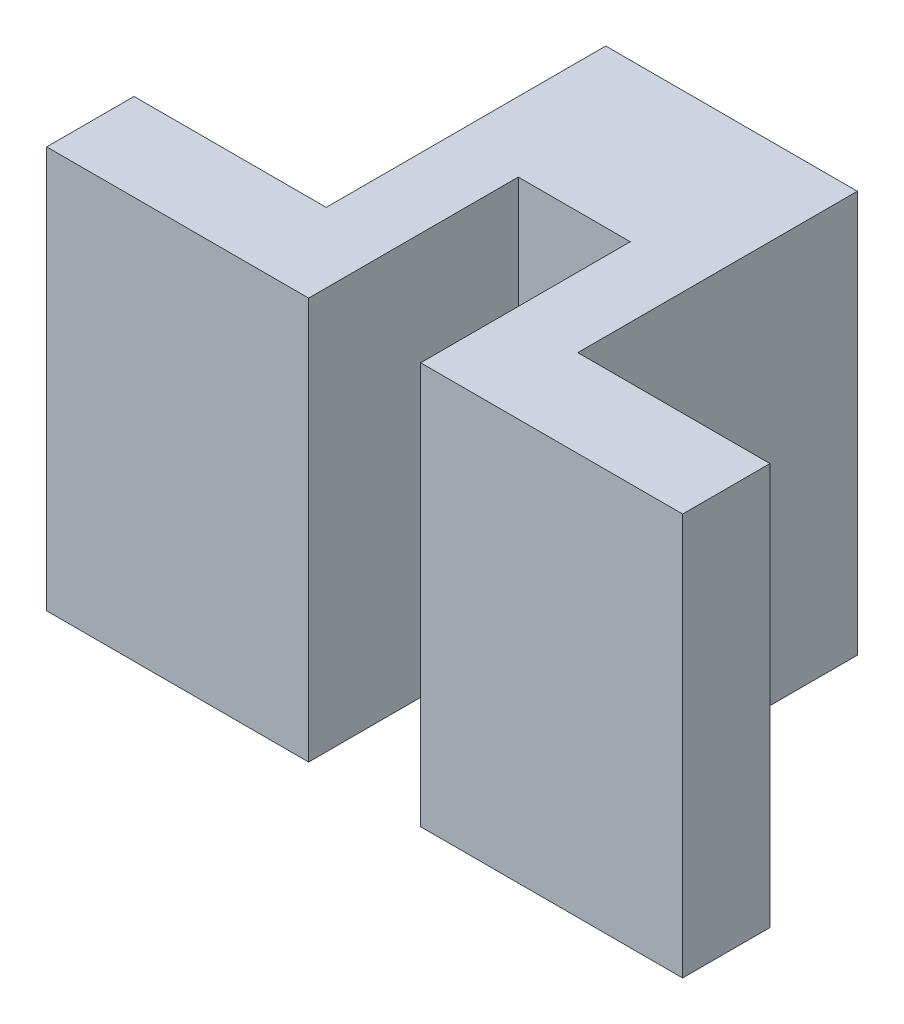
SolidWorks part; units mm, degrees
ref_plane "Front Plane" through (0, 0, 0) normal (0, 0, 1) x (1, 0, 0)
ref_plane "Top Plane" through (0, 0, 0) normal (0, 1, 0) x (1, 0, 0)
ref_plane "Right Plane" through (0, 0, 0) normal (1, 0, 0) x (0, 0, -1)
sketch "Sketch1" plane through (0, 0, 0) normal (0, 0, 1) x (1, 0, 0)
  line L0 (-8.75, 8.5) -> (-8.75, 11.5) construction
  line L1 (-8.5, 8.5) -> (-17.6, 8.5)
  line L2 (-8.5, 8.5) -> (-8.5, 14.25)
  line L3 (-8.5, 14.25) -> (-17.6, 14.25)
  line L4 (-17.6, 8.5) -> (-17.6, 14.25)
  line L6 (-17.85, 11.5) -> (-17.85, 8.5) construction
  line L7 (-17.85, 8.5) -> (-15.25, 8.5) construction
  line L8 (-15.25, 14.5) -> (-17.85, 14.5) construction
  dimension "D1" = 0.25
  dimension "D2" = 0.25
  dimension "D3" = 0.25
extrude "Boss-Extrude1" add sketch "Sketch1" along normal blind 1.25
sketch "Sketch3" plane through (0, 0, 0) normal (0, 0, -1) x (-1, 0, 0)
  line L0 (8.5, 14.25) -> (17.6, 14.25) construction
  line L1 (14.85, 14.25) -> (11.25, 14.25)
  line L2 (14.85, 14.25) -> (14.85, 8.5)
  line L3 (14.85, 8.5) -> (11.25, 8.5)
  line L4 (11.25, 14.25) -> (11.25, 8.5)
  line L5 (17.6, 8.5) -> (8.5, 8.5) construction
  line L8 (8.5, 8.5) -> (8.5, 14.25) construction
  line L9 (17.6, 14.25) -> (17.6, 8.5) construction
  dimension "D1" = 2.75
  dimension "D2" = 2.75
extrude "Boss-Extrude2" add sketch "Sketch3" along normal blind 4
sketch "Sketch2" plane through (0, 0, 1.25) normal (0, 0, 1) x (1, 0, 0)
  line L0 (-8.5, 8.5) -> (-8.5, 14.25) construction
  line L1 (-13.8517, 3.875) -> (-12.2483, 3.875)
  line L2 (-13.8517, 3.875) -> (-13.8517, 18.875)
  line L3 (-13.8517, 18.875) -> (-12.2483, 18.875)
  line L4 (-12.2483, 3.875) -> (-12.2483, 18.875)
  line L5 (-8.5, 14.25) -> (-17.6, 14.25) construction
  point P4 (-12.2483, 11.375)
  point P7 (-8.5, 11.375)
  point P8 (-13.05, 18.875)
  point P11 (-13.05, 14.25)
  dimension "D1" = 15
  dimension "D2" = 1.6033
extrude "Cut-Extrude1" cut sketch "Sketch2" against normal blind 3
